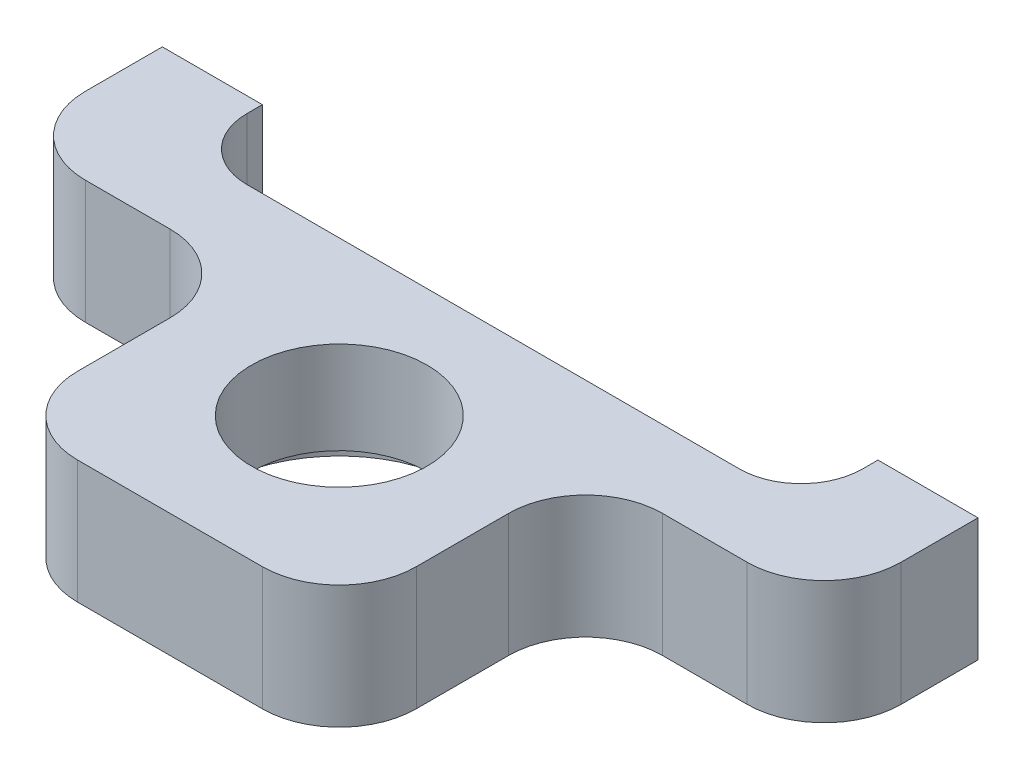
SolidWorks part; units mm, degrees
material "6061 Alloy"
ref_plane "Front Plane" through (0, 0, 0) normal (0, 0, 1) x (1, 0, 0)
ref_plane "Top Plane" through (0, 0, 0) normal (0, 1, 0) x (1, 0, 0)
ref_plane "Right Plane" through (0, 0, 0) normal (1, 0, 0) x (0, 0, -1)
ref_plane "Plane1" through (0, 0, 0) normal (0, -1, 0) x (1, 0, 0)
sketch "Sketch1" plane through (0, 0, 0) normal (0, -1, 0) x (1, 0, 0)
  line L0 (26.5, 0) -> (26.5, 26)
  line L1 (26.5, 26) -> (-26.5, 26)
  line L2 (-26.5, 26) -> (-26.5, 0)
  line L3 (-26.5, 0) -> (26.5, 0)
extrude "Boss-Extrude1" add sketch "Sketch1" against normal blind 8
sketch "Sketch2" plane through (0, 8, 0) normal (0, 1, 0) x (-1, 0, 0)
  line L0 (-11, 10) -> (-11, 26)
  line L1 (-11, 26) -> (-26.5, 26)
  line L2 (-26.5, 26) -> (-26.5, 10)
  line L3 (-26.5, 10) -> (-11, 10)
extrude "Cut-Extrude1" cut sketch "Sketch2" against normal through all
sketch "Sketch3" plane through (0, 8, 0) normal (0, 1, 0) x (-1, 0, 0)
  line L0 (11, 26) -> (11, 10)
  line L1 (11, 10) -> (26.5, 10)
  line L2 (26.5, 10) -> (26.5, 26)
  line L3 (26.5, 26) -> (11, 26)
extrude "Cut-Extrude2" cut sketch "Sketch3" against normal through all
sketch "Sketch4" plane through (0, 8, 0) normal (0, 1, 0) x (-1, 0, 0)
  line L0 (20, 0) -> (20, 5)
  line L1 (20, 5) -> (-20, 5)
  line L2 (-20, 5) -> (-20, 0)
  line L3 (-20, 0) -> (20, 0)
extrude "Cut-Extrude3" cut sketch "Sketch4" against normal through all
hole_wizard "CBORE for M10 Hex Head Bolt1" positions "Sketch6" profile "Sketch5" counterbore size "M10" standard "ANSI Metric" end condition through all
sketch "Sketch6" plane through (0, 0, 0) normal (0, -1, 0) x (-1, 0, 0)
  point P0 (0, -15)
sketch "Sketch5" plane through (0, 0, 15) normal (1, 0, 0) x (0, 0, -1)
  line L0 (0, 0) -> (0, 8)
  line L1 (0, 8) -> (5.7, 8)
  line L3 (5.7, 8) -> (5.7, 2)
  line L4 (5.7, 2) -> (8.1, 2)
  line L5 (8.1, 2) -> (8.1, 0)
  line L7 (8.1, 0) -> (0, 0)
  line L11 (0, -6.35) -> (0, 107.95) construction
  dimension "Thru Hole Dia." = 11.4
  dimension "Thru Hole Depth" = 8
  dimension "C'Bore Dia." = 16.2
  dimension "C'Bore Depth" = 2
hole_wizard "M4x0.7 Tapped Hole1" positions "Sketch8" profile "Sketch7" tap size "M4x0.7" standard "ANSI Metric"
sketch "Sketch8" plane through (0, 0, 0) normal (0, 0, -1) x (-1, 0, 0)
  point P0 (-23.25, 4)
  point P1 (23.25, 4)
sketch "Sketch7" plane through (23.25, 4, 0) normal (1, 0, 0) x (0, 1, 0)
  line L0 (0, 0) -> (0, 6.9914)
  line L1 (0, 6.9914) -> (1.65, 6)
  line L2 (1.65, 6) -> (1.65, 0)
  line L5 (1.65, 0) -> (0, 0)
  line L10 (0, 6.9914) -> (-1.65, 6) construction
  line L11 (0, -6.35) -> (0, 107.95) construction
  dimension "Tap Drill Dia." = 3.3
  dimension "Tap Drill Depth" = 6
  dimension "Drill Angle" = 118
fillet "Fillet1" radius 4 2 edges at (-20, 4, 5) (20, 4, 5)
fillet "Fillet2" radius 5 6 edges at (11, 4, 10) (11, 4, 26) (-11, 4, 26) (-11, 4, 10) (26.5, 4, 10) (-26.5, 4, 10)
